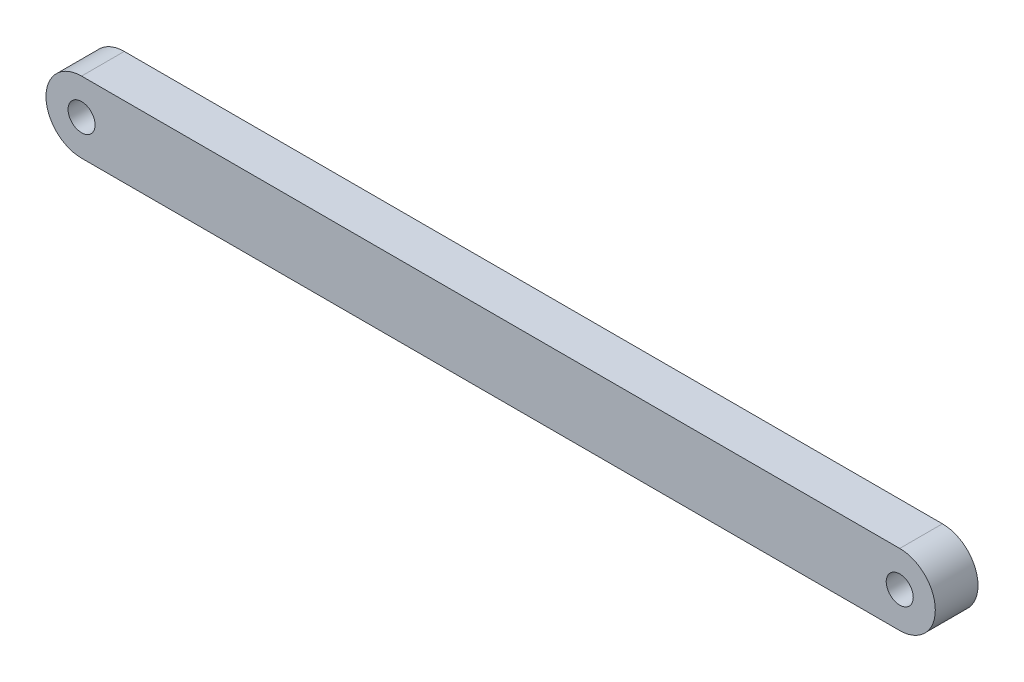
SolidWorks part; units mm, degrees
material "MDF"
ref_plane "Front Plane" through (0, 0, 0) normal (0, 0, 1) x (1, 0, 0)
ref_plane "Top Plane" through (0, 0, 0) normal (0, 1, 0) x (1, 0, 0)
ref_plane "Right Plane" through (0, 0, 0) normal (1, 0, 0) x (0, 0, -1)
sketch "Sketch1" plane through (0, 0, 0) normal (0, 0, 1) x (1, 0, 0)
  line L0 (0, -5) -> (0, 5) construction
  line L1 (-57.5, 5) -> (57.5, 5)
  line L2 (-57.5, -5) -> (57.5, -5)
  line L3 (57.5, 0) -> (-57.5, 0) construction
  arc A0 (57.5, 5) -> (57.5, -5) centre (57.5, 0) cw
  arc A1 (-57.5, 5) -> (-57.5, -5) centre (-57.5, 0) ccw
  circle A2 centre (-57.5, 0) radius 1.9
  circle A3 centre (57.5, 0) radius 1.9
  point P4 (0, 0)
  point P8 (0, 5)
  point P11 (0, -5)
  point P13 (0, 0)
  dimension "D3" = 3.8
  dimension "D4" = 3.8
  dimension "D1" = 10
  dimension "D2" = 115
extrude "Boss-Extrude1" add sketch "Sketch1" along normal blind 6
sketch "Sketch2" plane through (0, 0, 6) normal (0, 0, 1) x (1, 0, 0)
  line L0 (28.75, 0) -> (-28.75, 0) construction
  line L1 (-57.5, 1.9) -> (-57.5, -1.9) construction
  line L2 (-52.5, -2.5) -> (-5, -2.5)
  line L3 (-52.5, -2.5) -> (-52.5, 2.5)
  line L4 (-52.5, 2.5) -> (-5, 2.5)
  line L5 (-5, -2.5) -> (-5, 2.5)
  line L6 (-52.5, -2.5) -> (-5, 2.5) construction
  line L7 (-52.5, 2.5) -> (-5, -2.5) construction
  line L8 (5, -2.5) -> (52.5, -2.5)
  line L9 (5, -2.5) -> (5, 2.5)
  line L10 (5, 2.5) -> (52.5, 2.5)
  line L11 (52.5, -2.5) -> (52.5, 2.5)
  line L12 (5, -2.5) -> (52.5, 2.5) construction
  line L13 (5, 2.5) -> (52.5, -2.5) construction
  line L14 (57.5, 1.9) -> (57.5, -1.9) construction
  circle A0 centre (-57.5, 0) radius 1.9 construction
  circle A1 centre (57.5, 0) radius 1.9 construction
  point P4 (0, 0)
  dimension "D1" = 5
  dimension "D2" = 5
  dimension "D3" = 10
  dimension "D4" = 5
  dimension "D5" = 5
extrude "Cut-Extrude1" [suppressed] cut sketch "Sketch2" against normal through all
